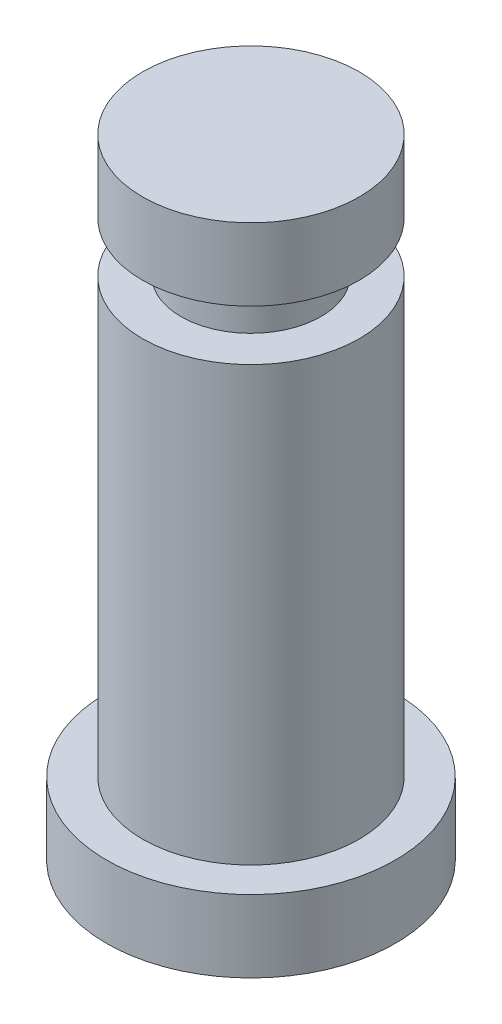
SolidWorks part; units mm, degrees
material "K110"
ref_plane "Front Plane" through (0, 0, 0) normal (0, 0, 1) x (1, 0, 0)
ref_plane "Top Plane" through (0, 0, 0) normal (0, 1, 0) x (1, 0, 0)
ref_plane "Right Plane" through (0, 0, 0) normal (1, 0, 0) x (0, 0, -1)
sketch "Sketch1" plane through (0, 0, 0) normal (0, 0, 1) x (1, 0, 0)
  line L0 (0, 0) -> (10, 0)
  line L1 (10, 0) -> (10, 5)
  line L2 (10, 5) -> (7.5, 5)
  line L3 (7.5, 5) -> (7.5, 43.5)
  line L4 (7.5, 43.5) -> (0, 43.5)
  line L5 (0, 43.5) -> (0, 0)
  line L6 (0, 48.5) -> (0, -5) construction
  point P9 (8.75, 5)
  dimension "D1" = 5
  dimension "D2" = 5
  dimension "D3" = 20
  dimension "D4" = 15
  dimension "D5" = 5
  dimension "D6" = 38.5
revolve "Revolve1" add sketch "Sketch1" angle 360 about L6
sketch "Sketch2" plane through (0, 0, 0) normal (0, 0, 1) x (1, 0, 0)
  line L0 (7.5, 5) -> (7.5, 43.5) construction
  line L1 (7.5, 35) -> (4.85, 35)
  line L2 (7.5, 35) -> (7.5, 38.5)
  line L3 (7.5, 38.5) -> (4.85, 38.5)
  line L4 (4.85, 35) -> (4.85, 38.5)
  line L5 (0, 43.5) -> (0, 5) construction
  line L6 (7.5, 43.5) -> (-7.5, 43.5) construction
  line L7 (10, 5) -> (-10, 5) construction
  dimension "D1" = 3.5
  dimension "D2" = 2.65
  dimension "D3" = 30
revolve "Cut-Revolve1" cut sketch "Sketch2" angle 360 about L5
